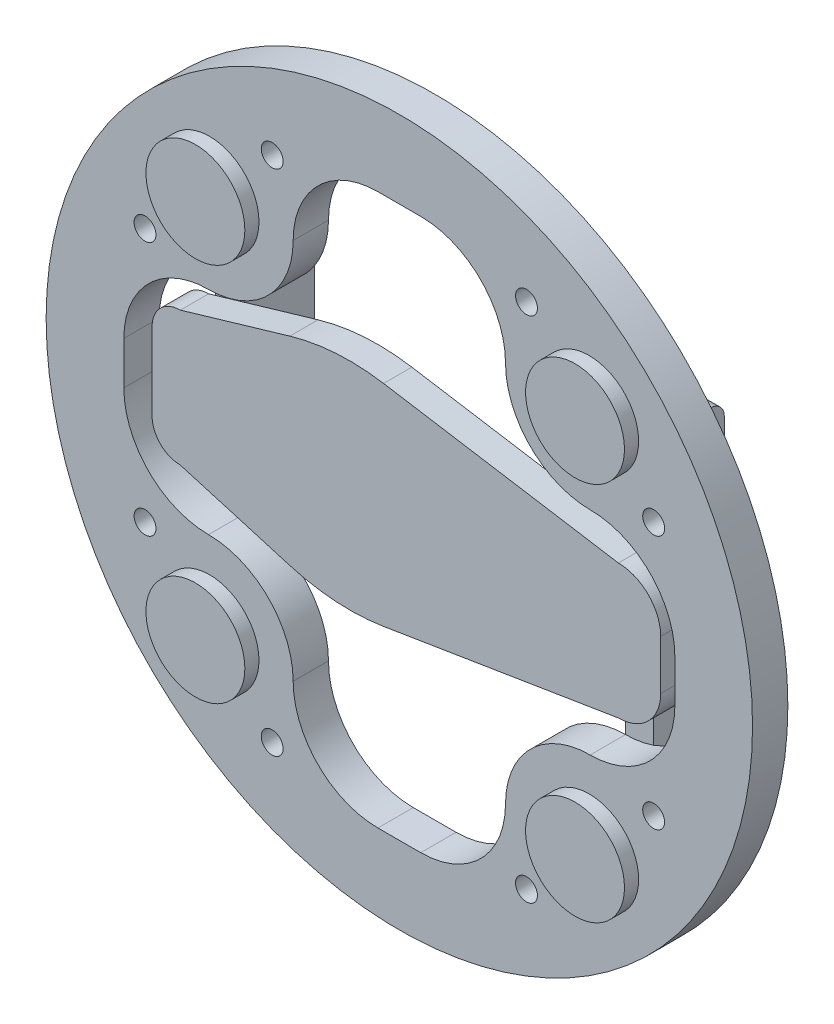
SolidWorks part; units mm, degrees
ref_plane "Alzado" through (0, 0, 0) normal (0, 0, 1) x (1, 0, 0)
ref_plane "Planta" through (0, 0, 0) normal (0, 1, 0) x (1, 0, 0)
ref_plane "Vista lateral" through (0, 0, 0) normal (1, 0, 0) x (0, 0, -1)
sketch "Croquis1" plane through (0, 0, 0) normal (0, 0, 1) x (1, 0, 0)
  line L9 (18, 36) -> (-18, 36)
  line L10 (18, 36) -> (18, -36)
  line L11 (18, -36) -> (-18, -36)
  line L12 (-18, 36) -> (-18, -36)
  line L13 (18, 36) -> (-18, -36) construction
  line L14 (18, -36) -> (-18, 36) construction
  circle A0 centre (0, 0) radius 50
  circle A2 centre (-26.87, 26.87) radius 7
  circle A3 centre (26.87, 26.87) radius 7
  circle A4 centre (26.87, -26.87) radius 7
  circle A5 centre (-26.87, -26.87) radius 7
  circle A6 centre (-36, 18) radius 1.55
  circle A7 centre (18, 36) radius 1.55
  circle A8 centre (36, -18) radius 1.55
  circle A9 centre (-18, -36) radius 1.55
  circle A10 centre (-18, 36) radius 1.55
  circle A11 centre (36, 18) radius 1.55
  circle A12 centre (18, -36) radius 1.55
  circle A13 centre (-36, -18) radius 1.55
  dimension "D1" = 100
  dimension "D2" = 36
  dimension "D3" = 72
  dimension "D4" = 14
  dimension "D6" = 3.1
  dimension "D8" = 3.1
  dimension "D5" = 4
  dimension "D7" = 4
  dimension "D9" = 4
extrude "Saliente-Extruir1" add sketch "Croquis1" along normal blind 7 contours A2 | A5 | A4 | A3
sketch "Croquis3" plane through (0, 0, 0) normal (0, 0, 1) x (1, 0, 0)
  line L4 (18, 36) -> (-18, -36) construction
  line L5 (18, -36) -> (-18, 36) construction
  circle A0 centre (0, 0) radius 50
  circle A1 centre (-26.87, 26.87) radius 7
  circle A2 centre (26.87, 26.87) radius 7
  circle A3 centre (26.87, -26.87) radius 7
  circle A4 centre (-26.87, -26.87) radius 7
  circle A5 centre (-36, 18) radius 1.55
  circle A6 centre (18, 36) radius 1.55
  circle A7 centre (36, -18) radius 1.55
  circle A8 centre (-18, -36) radius 1.55
  circle A9 centre (-18, 36) radius 1.55
  circle A10 centre (36, 18) radius 1.55
  circle A11 centre (18, -36) radius 1.55
  circle A12 centre (-36, -18) radius 1.55
  dimension "D1" = 100
  dimension "D2" = 14
  dimension "D3" = 3.1
  dimension "D6" = 3.1
  dimension "D4" = 36
  dimension "D5" = 72
extrude "Saliente-Extruir2" add sketch "Croquis3" along normal blind 5
sketch "Croquis5" plane through (0, 0, 5) normal (0, 0, 1) x (1, 0, 0)
  line L1 (-39, -15.03) -> (39, -15.03)
  line L2 (-39, -15.03) -> (-39, 15.03)
  line L3 (-39, 15.03) -> (39, 15.03)
  line L4 (39, -15.03) -> (39, 15.03)
  line L5 (-39, -15.03) -> (39, 15.03) construction
  line L6 (-39, 15.03) -> (39, -15.03) construction
  point P0 (0, 0)
  dimension "D1" = 78
  dimension "D2" = 30.06
extrude "Cortar-Extruir1" cut sketch "Croquis5" against normal blind 5
sketch "Croquis6" plane through (0, 0, 5) normal (0, 0, 1) x (1, 0, 0)
  line L1 (15.03, 39) -> (-15.03, 39)
  line L2 (15.03, 39) -> (15.03, -39)
  line L3 (15.03, -39) -> (-15.03, -39)
  line L4 (-15.03, 39) -> (-15.03, -39)
  line L5 (15.03, 39) -> (-15.03, -39) construction
  line L6 (15.03, -39) -> (-15.03, 39) construction
  point P0 (0, 0)
  dimension "D1" = 30.06
  dimension "D2" = 78
extrude "Cortar-Extruir2" cut sketch "Croquis6" against normal blind 5
fillet "Redondeo1" radius 12 4 edges at (-15.03, 15.03, 2.5) (-15.03, -15.03, 2.5) (15.03, -15.03, 2.5) (15.03, 15.03, 2.5)
fillet "Redondeo2" radius 12 8 edges at (-39, -15.03, 2.5) (-39, 15.03, 2.5) (39, -15.03, 2.5) (39, 15.03, 2.5) (15.03, 39, 2.5) (-15.03, 39, 2.5) (15.03, -39, 2.5) (-15.03, -39, 2.5)
sketch "Croquis7" plane through (0, 0, 0) normal (0, 0, -1) x (-1, 0, 0)
  line L0 (-39, -3.03) -> (-39, 3.03) construction
  line L1 (-31, 23) -> (-27, 23)
  line L2 (-31, 23) -> (-31, -23)
  line L3 (-31, -23) -> (-27, -23)
  line L4 (-27, 23) -> (-27, -23)
  point P6 (-27, 0)
  dimension "D1" = 8
  dimension "D2" = 4
  dimension "D3" = 46
extrude "Saliente-Extruir3" add sketch "Croquis7" along normal blind 10
fillet "Redondeo3" radius 2 2 edges at (29, -23, -10) (29, 23, -10)
mirror "Simetría1" about plane through (0, 0, 0) normal (1, 0, 0) of "Redondeo3", "Saliente-Extruir3"
sketch "Croquis8" plane through (0, 0, 0) normal (0, 0, 1) x (1, 0, 0)
  line L0 (-9.96, 15.985) -> (-9.96, 15.2181) construction
  line L2 (-36, 5.5) -> (-36, -5.5)
  line L4 (36, 3.5) -> (36, -3.5)
  line L5 (-36, 9.5) -> (-33.9903, 8.9697) construction
  line L6 (-36, -9.5) -> (-33.9903, -8.9697) construction
  line L7 (-32, 9.5) -> (-16.5023, 14.06)
  line L8 (-3.2284, 14.8925) -> (30, 9.5)
  line L9 (-32, -9.5) -> (-16.5023, -14.06)
  line L10 (-3.2284, -14.8925) -> (30, -9.5)
  line L11 (-9.96, -15.2181) -> (-9.96, -15.985) construction
  line L15 (32.9855, 8.7045) -> (36, 9.5) construction
  line L16 (32.9855, -8.7045) -> (36, -9.5) construction
  arc A0 (-36, -5.5) -> (-32, -9.5) centre (-32, -5.5) ccw
  arc A1 (-32, 9.5) -> (-36, 5.5) centre (-32, 5.5) ccw
  arc A2 (30, 9.5) -> (36, 3.5) centre (30, 3.5) cw
  arc A3 (30, -9.5) -> (36, -3.5) centre (30, -3.5) ccw
  arc A4 (-16.5023, 14.06) -> (-3.2284, 14.8925) centre (-8.0342, -14.72) cw
  arc A5 (-16.5023, -14.06) -> (-3.2284, -14.8925) centre (-8.0342, 14.72) ccw
  point P0 (0, 0)
  dimension "D3" = 4
  dimension "D4" = 6
  dimension "D7" = 30
  dimension "D1" = 72
  dimension "D2" = 19
  dimension "D5" = 26.04
  dimension "D6" = 31.97
extrude "Saliente-Extruir4" add sketch "Croquis8" along normal blind 4
